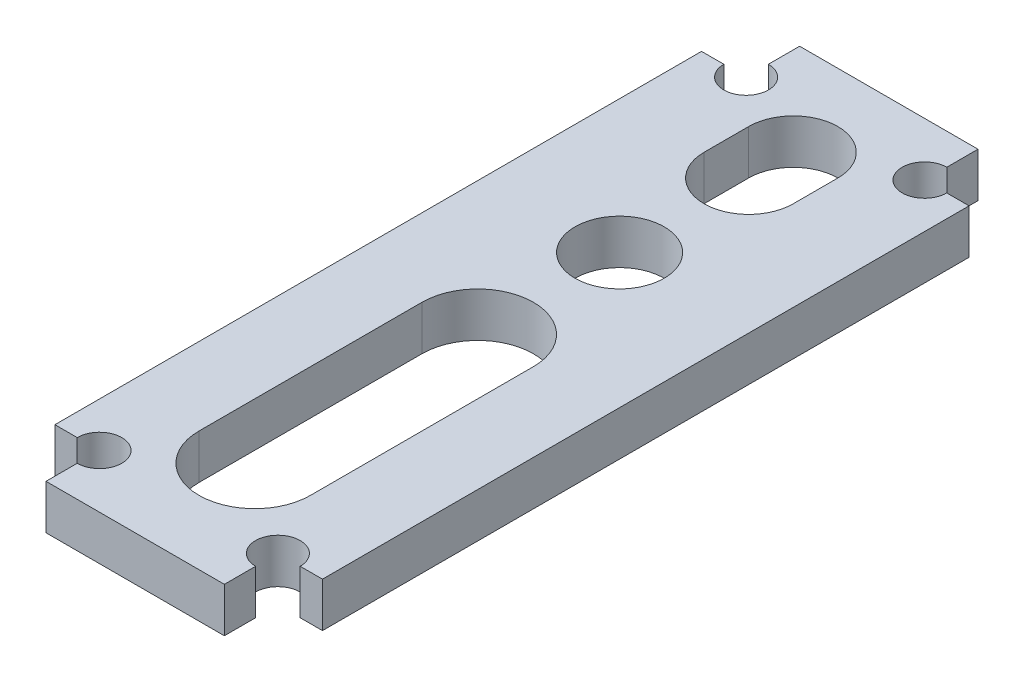
SolidWorks part; units mm, degrees
ref_plane "前视基准面" through (0, 0, 0) normal (0, 0, 1) x (1, 0, 0)
ref_plane "上视基准面" through (0, 0, 0) normal (0, 1, 0) x (1, 0, 0)
ref_plane "右视基准面" through (0, 0, 0) normal (1, 0, 0) x (0, 0, -1)
other "Configuration Table"
sketch "草图1" plane through (0, 0, 0) normal (0, 1, 0) x (1, 0, 0)
  line L20 (-2, 15.8877) -> (-2, 16.3877)
  line L24 (-3, 14.3877) -> (-3, 3.3877)
  line L26 (3, 3.3877) -> (3, 14.3877)
  line L29 (-2, 16.3877) -> (-2, 16.5877)
  line L32 (-3, 3.3877) -> (-3, 2.0878)
  line L33 (-1.0024, 2.0878) -> (-4.0024, 2.0878) construction
  line L34 (3, 3.3877) -> (3, 2.0878)
  line L35 (-1.0024, 2.0878) -> (32.9976, 2.0878) construction
  line L39 (-0.0118, 2.3805) -> (-0.0118, 7.3805) construction
  line L42 (-0.0118, 13.4567) -> (-0.0118, 14.4567) construction
  line L45 (-3, 14.3877) -> (-3, 15.3877)
  line L48 (-3, 15.3877) -> (-2.5, 15.3877)
  line L49 (-1.2618, 2.3805) -> (-1.2618, 7.3805)
  line L52 (-2, 16.5877) -> (2, 16.5877)
  line L53 (-3, 2.0878) -> (-3, 0.8878)
  line L59 (3, 0.8878) -> (3, 2.0878)
  line L61 (-3.0024, 0.8878) -> (-2.5, 0.8878)
  line L62 (-2, 0.3878) -> (-2, -0.3122)
  line L63 (2.4636, -0.3122) -> (-2.5364, -0.3122) construction
  line L64 (-2, -0.3122) -> (2, -0.3122)
  line L65 (2, -0.3122) -> (2, 0.3878)
  line L66 (-2.5024, 0.8878) -> (33.4976, 0.8878) construction
  line L67 (2.5, 0.8878) -> (3, 0.8878)
  line L69 (2, 16.5877) -> (2, 15.8877)
  line L73 (2, 15.3877) -> (3, 15.3877)
  line L74 (3, 15.3877) -> (3, 14.3877)
  line L75 (1.2382, 2.3805) -> (1.2382, 7.3805)
  line L77 (-1.0118, 13.4567) -> (-1.0118, 14.4567)
  line L80 (0.9882, 13.4567) -> (0.9882, 14.4567)
  circle A14 centre (-0.0118, 10.5628) radius 1
  arc A15 (-2, 0.3878) -> (-2.5, 0.8878) centre (-2, 0.8878) ccw
  arc A16 (2.5, 0.8878) -> (2, 0.3878) centre (2, 0.8878) ccw
  arc A21 (-2.5, 15.3877) -> (-2, 15.8877) centre (-2, 15.3877) ccw
  arc A22 (2, 15.8877) -> (2.5, 15.3877) centre (2, 15.3877) ccw
  arc A23 (-1.2618, 2.3805) -> (1.2382, 2.3805) centre (-0.0118, 2.3805) ccw
  arc A24 (1.2382, 7.3805) -> (-1.2618, 7.3805) centre (-0.0118, 7.3805) ccw
  arc A27 (-1.0118, 13.4567) -> (0.9882, 13.4567) centre (-0.0118, 13.4567) ccw
  arc A28 (0.9882, 14.4567) -> (-1.0118, 14.4567) centre (-0.0118, 14.4567) ccw
  point P4 (0, 0)
  point P35 (-0.0118, 4.8805)
  point P44 (-0.0118, 13.9567)
extrude "凸台-拉伸1" add sketch "草图1" along normal blind 1
